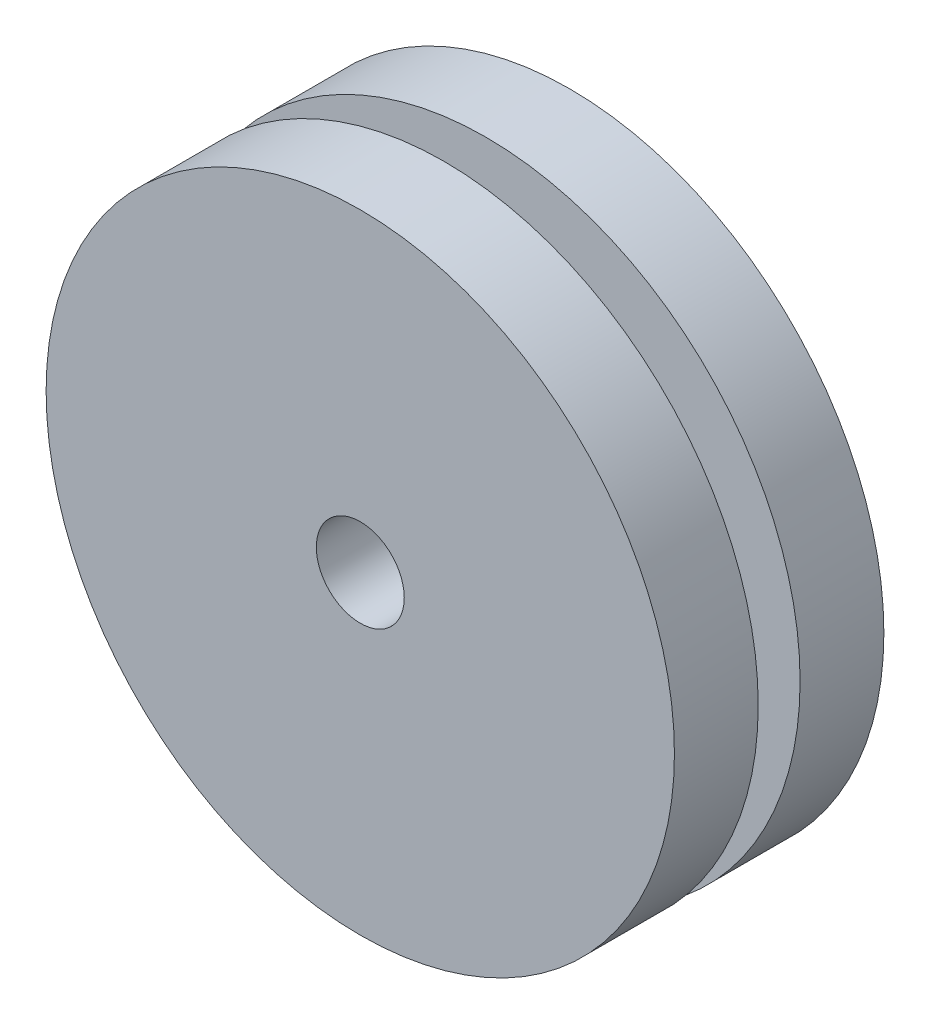
SolidWorks part; units mm, degrees
material "NEOPRENE"
ref_plane "Front Plane" through (0, 0, 0) normal (0, 0, 1) x (1, 0, 0)
ref_plane "Top Plane" through (0, 0, 0) normal (0, 1, 0) x (1, 0, 0)
ref_plane "Right Plane" through (0, 0, 0) normal (1, 0, 0) x (0, 0, -1)
sketch "Sketch1" plane through (0, 0, 0) normal (0, 0, 1) x (1, 0, 0)
  circle A0 centre (0, 0) radius 19.05
  dimension "D1" = 38.1
extrude "Boss-Extrude1" add sketch "Sketch1" along normal blind 12.7
sketch "Sketch2" plane through (0, 0, 0) normal (0, 1, 0) x (1, 0, 0)
  line L0 (19.05, -7.62) -> (6.35, -7.62)
  line L1 (19.05, -12.7) -> (19.05, 0) construction
  line L2 (6.35, -7.62) -> (6.35, -5.08)
  line L3 (6.35, -5.08) -> (19.05, -5.08)
  line L4 (19.05, -5.08) -> (19.05, -7.62)
  line L5 (19.05, 0) -> (-19.05, 0) construction
  line L6 (0, 0) -> (0, -12.7)
  line L7 (-19.05, -12.7) -> (19.05, -12.7) construction
  dimension "D1" = 5.08
  dimension "D2" = 2.54
  dimension "D3" = 12.7
revolve "Cut-Revolve1" cut sketch "Sketch2" angle 360 about L6
sketch "Sketch3" plane through (0, 0, 12.7) normal (0, 0, 1) x (1, 0, 0)
  circle A0 centre (0, 0) radius 2.667
  circle A1 centre (0, 0) radius 19.05 construction
  dimension "D1" = 5.334
extrude "Cut-Extrude1" cut sketch "Sketch3" against normal through all contours A0
sketch "Sketch4" plane through (0, 0, 0) normal (0, 0, -1) x (-1, 0, 0)
  line L1 (-4.445, 3.0504) -> (-2.54, 6.35)
  line L2 (-2.54, 6.35) -> (-4.445, 9.6496)
  line L3 (-4.445, 9.6496) -> (-8.255, 9.6496)
  line L4 (-8.255, 9.6496) -> (-10.16, 6.35)
  line L5 (-10.16, 6.35) -> (-8.255, 3.0504)
  line L6 (-8.255, 3.0504) -> (-4.445, 3.0504)
  circle A0 centre (-6.35, 6.35) radius 3.2996 construction
  dimension "D1" = 3.81
  dimension "D2" = 6.35
  dimension "D3" = 6.35
extrude "Boss-Extrude2" add sketch "Sketch4" along normal blind 2.54 draft 20
pattern_circular "CirPattern1" count 6 over 360 about axis through (0, 0, 0) along (0, 0, 1) of "Boss-Extrude2"
